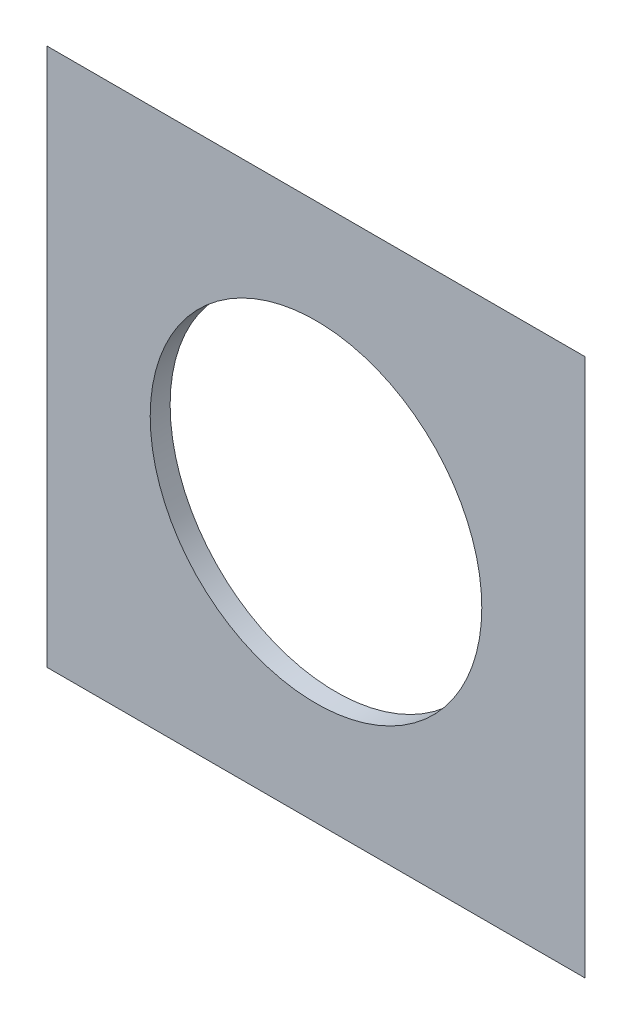
SolidWorks part; units mm, degrees
ref_plane "Front Plane" through (0, 0, 0) normal (0, 0, 1) x (1, 0, 0)
ref_plane "Top Plane" through (0, 0, 0) normal (0, 1, 0) x (1, 0, 0)
ref_plane "Right Plane" through (0, 0, 0) normal (1, 0, 0) x (0, 0, -1)
sketch "Sketch1" plane through (0, 0, 0) normal (0, 0, 1) x (1, 0, 0)
  line L0 (-171.45, 171.45) -> (171.45, -171.45) construction
  line L1 (-171.45, 171.45) -> (171.45, 171.45)
  line L2 (-171.45, 171.45) -> (-171.45, -171.45)
  line L3 (-171.45, -171.45) -> (171.45, -171.45)
  line L4 (171.45, 171.45) -> (171.45, -171.45)
  line L5 (-171.45, -171.45) -> (-171.45, 171.45) construction
  line L10 (-171.45, 171.45) -> (171.45, 171.45) construction
extrude "Boss-Extrude1" add sketch "Sketch1" against normal blind 12.7
draft "Draft1" type of draft neutral plane draft angle 45 faces to draft 4 face at (-171.45, 0, -6.35) face at (0, -171.45, -6.35) face at (171.45, 0, -6.35) face at (0, 171.45, -6.35) neutral plane through (0, 0, 0) neutral plane normal (0, 0, 1) reverse direction yes parameters "D1"=45
sketch "Sketch2" plane through (0, 0, -12.7) normal (0, 0, -1) x (-1, 0, 0)
  circle A1 centre (0, 0) radius 104.5108 construction
  circle A2 centre (0, 0) radius 105.6538
  dimension "D1" = 1.143
extrude "Cut-Extrude1" cut sketch "Sketch2" against normal through all
sketch "Sketch3" plane through (0, 0, -12.7) normal (0, 0, -1) x (-1, 0, 0)
  line L0 (18.6329, -145.1669) -> (145.1669, -18.6329)
  line L4 (28.152, -154.686) -> (154.686, -28.152)
  line L6 (34.2705, -130.0682) -> (132.6668, -31.6719) construction
  line L7 (22.7117, -141.627) -> (163.449, -0.8897) construction
  line L8 (34.2705, -130.0682) -> (43.2508, -139.0484) construction
  line L9 (31.692, -150.6072) -> (163.449, -18.8502) construction
  line L10 (43.2508, -139.0484) -> (141.6471, -40.6521) construction
  line L11 (141.6471, -40.6521) -> (132.6668, -31.6719) construction
  line L12 (-171.45, -171.45) -> (171.45, 171.45) construction
  line L21 (171.45, -171.45) -> (91.2477, -91.0515) construction
  line L25 (171.45, -171.45) -> (-171.45, -171.45) construction
  line L26 (154.686, -28.152) -> (171.45, -28.152) construction
  line L27 (171.45, 171.45) -> (171.45, -171.45) construction
  line L28 (28.152, -154.686) -> (28.152, -171.45) construction
  line L29 (-154.686, 28.152) -> (-171.45, 28.152) construction
  line L30 (-28.152, 154.686) -> (-28.152, 171.45) construction
  line L31 (-171.45, 171.45) -> (-91.0515, 91.2477) construction
  line L32 (-40.6521, 141.6471) -> (-31.6719, 132.6668) construction
  line L33 (-139.0484, 43.2508) -> (-40.6521, 141.6471) construction
  line L34 (-130.0682, 34.2705) -> (-139.0484, 43.2508) construction
  line L35 (-130.0682, 34.2705) -> (-31.6719, 132.6668) construction
  line L36 (-154.686, 28.152) -> (-28.152, 154.686)
  line L37 (-145.1669, 18.6329) -> (-18.6329, 145.1669)
  arc A0 (145.1669, -18.6329) -> (154.686, -28.152) centre (149.9265, -23.3925) cw
  arc A1 (18.6329, -145.1669) -> (28.152, -154.686) centre (23.3925, -149.9265) ccw
  arc A2 (-145.1669, 18.6329) -> (-154.686, 28.152) centre (-149.9265, 23.3925) cw
  arc A3 (-18.6329, 145.1669) -> (-28.152, 154.686) centre (-23.3925, 149.9265) ccw
  dimension "D3" = 16.764
  dimension "D1" = 0.381
  dimension "D2" = 0.381
extrude "Cut-Extrude2" cut sketch "Sketch3" against normal blind 5.08
